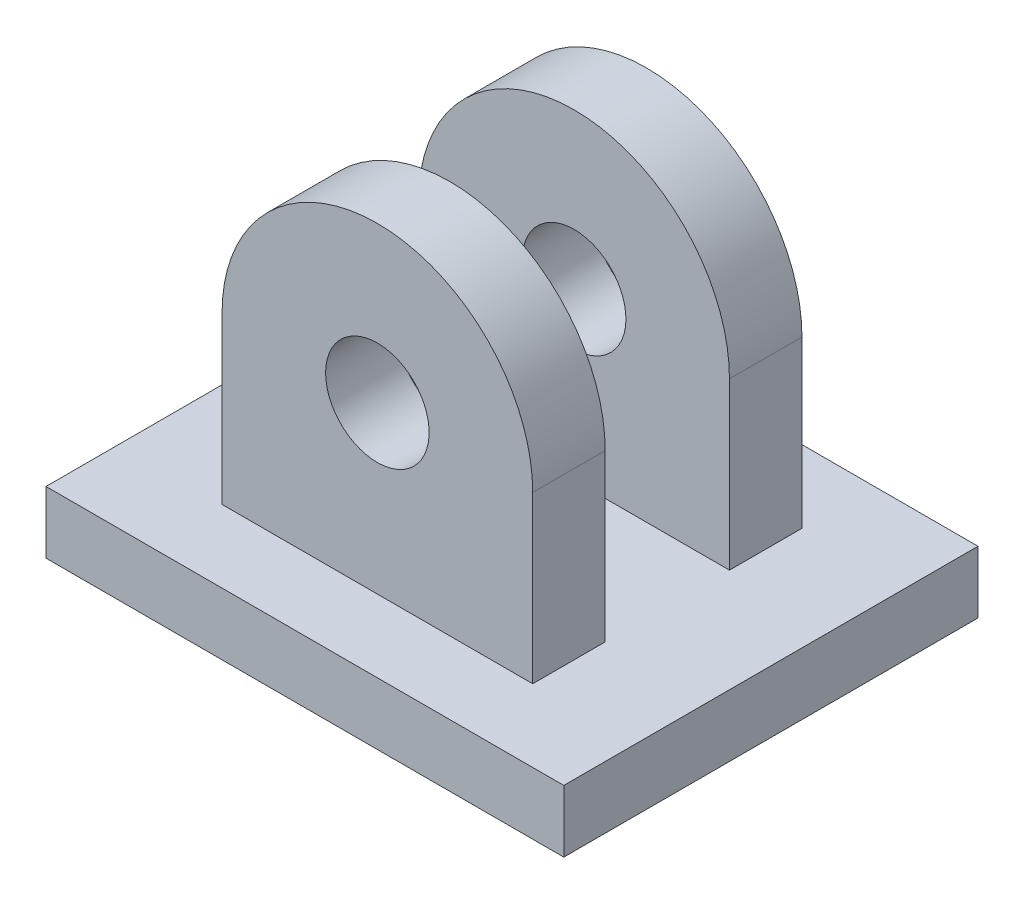
SolidWorks part; units mm, degrees
material "1060 Alloy"
ref_plane "Front Plane" through (0, 0, 0) normal (0, 0, 1) x (1, 0, 0)
ref_plane "Top Plane" through (0, 0, 0) normal (0, 1, 0) x (1, 0, 0)
ref_plane "Right Plane" through (0, 0, 0) normal (1, 0, 0) x (0, 0, -1)
sketch "Sketch1" plane through (0, 0, 0) normal (0, 0, 1) x (1, 0, 0)
  line L0 (15, -16) -> (25, -16)
  line L1 (15, 0) -> (15, -16)
  line L2 (-15, 0) -> (-15, -16)
  line L3 (-25, -16) -> (-15, -16)
  line L5 (-25, -16) -> (-25, -22)
  line L6 (-25, -22) -> (25, -22)
  line L7 (25, -22) -> (25, -16)
  circle A0 centre (0, 0) radius 5
  arc A1 (15, 0) -> (-15, 0) centre (0, 0) ccw
  dimension "D1" = 6
  dimension "D6" = 10
  dimension "D7" = 15
  dimension "D2" = 15
  dimension "D3" = 10
  dimension "D4" = 50
  dimension "D5" = 30
  dimension "D8" = 22
  dimension "D9" = 6
extrude "Extrude1" add sketch "Sketch1" along normal blind 40
sketch "Sketch2" plane through (15, 0, 0) normal (1, 0, 0) x (0, 0, -1)
  line L0 (-33, 18.4995) -> (-33, -16)
  line L4 (0, -16) -> (0, 0)
  line L5 (0, 0) -> (-40, 0)
  line L6 (-40, 0) -> (-40, -16)
  line L7 (-40, -16) -> (0, -16)
  line L8 (0, -16) -> (0, 18.4995)
  line L9 (-40, 18.4995) -> (-33, 18.4995)
  line L10 (-40, 18.4995) -> (-40, -16)
  line L11 (-40, -16) -> (-33, -16)
  line L33 (-26, 18.4995) -> (-26, -16)
  line L34 (-7, -16) -> (-7, 18.4995)
  line L35 (-14, -16) -> (-14, 18.4995)
  line L36 (0, -16) -> (0, 0) construction
  line L37 (-26, -16) -> (-14, -16)
  line L38 (-7, -16) -> (-7, 0) construction
  line L39 (-7, -16) -> (0, -16)
  line L40 (-14, -16) -> (-14, 0) construction
  line L41 (-26, 0) -> (-26, -16) construction
  line L42 (-33, 0) -> (-33, -16) construction
  line L43 (-40, 0) -> (-40, -16) construction
  line L44 (-7, 18.4995) -> (0, 18.4995)
  line L45 (-26, 18.4995) -> (-14, 18.4995)
  dimension "D5" = 12
  dimension "D1" = 0
  dimension "D2" = 7
  dimension "D3" = 7
  dimension "D4" = 7
extrude "Cut-Extrude1" cut sketch "Sketch2" against normal blind 40
